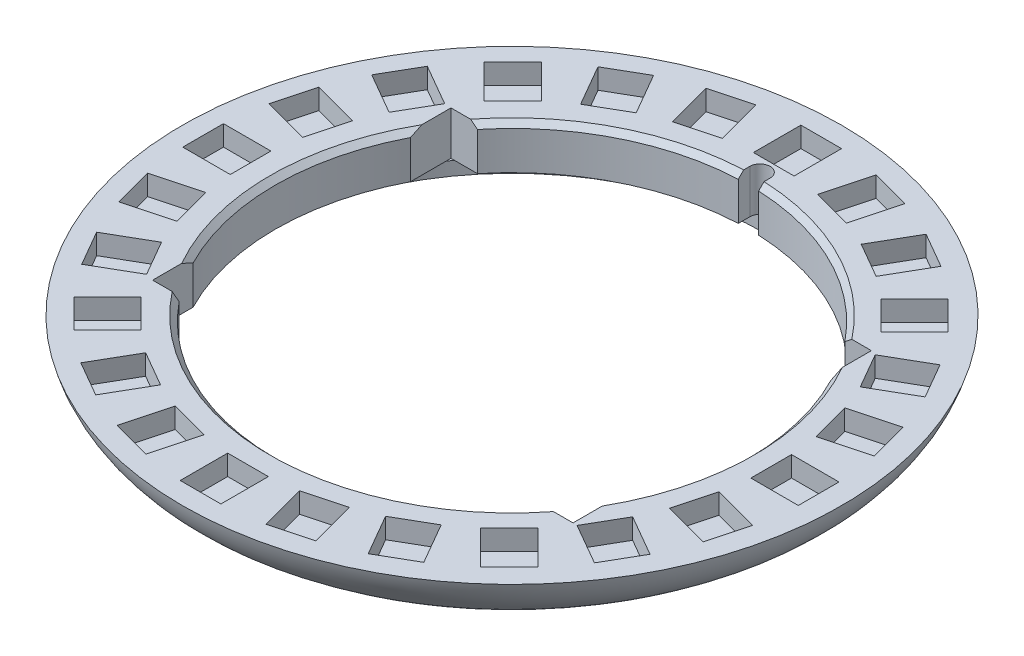
SolidWorks part; units mm, degrees
ref_plane "Plan de face" through (0, 0, 0) normal (0, 0, 1) x (1, 0, 0)
ref_plane "Plan de dessus" through (0, 0, 0) normal (0, 1, 0) x (1, 0, 0)
ref_plane "Plan de droite" through (0, 0, 0) normal (1, 0, 0) x (0, 0, -1)
sketch "Esquisse1" plane through (0, 0, 0) normal (0, 0, 1) x (1, 0, 0)
  line L0 (0, 0) -> (0, 12.722) construction
  line L1 (37.6, 0) -> (37.6, 2)
  line L2 (37.6, 2) -> (34.9, 2)
  line L3 (34.9, 2) -> (34.9, 8.4406)
  line L4 (34.9, 8.4406) -> (48.6, 8.4406)
  line L5 (37.6, 0) -> (39.8723, 0) construction
  line L6 (48.6, 8.4406) -> (47.2112, 3.2577) construction
  line L7 (48.6, 5.228) -> (48.6, 8.4406) construction
  arc A0 (37.6, 0) -> (48.6, 8.4406) centre (37.6, 11.388) ccw
  dimension "D1" = 11
  dimension "D4" = 75
  dimension "D2" = 75.2
  dimension "D3" = 2.7
  dimension "D5" = 2
revolve "Révolution1" add sketch "Esquisse1" angle 360 about L0
sketch "Esquisse2" plane through (0, 8.4406, 0) normal (0, 1, 0) x (1, 0, 0)
  line L1 (-31, -22) -> (31, -22)
  line L2 (-31, -22) -> (-31, 22)
  line L3 (-31, 22) -> (31, 22)
  line L4 (31, -22) -> (31, 22)
  line L5 (-31, -22) -> (31, 22) construction
  line L6 (-31, 22) -> (31, -22) construction
  point P0 (0, 0)
  dimension "D1" = 44
  dimension "D2" = 62
extrude "Enlèv. mat.-Extru.1" cut sketch "Esquisse2" against normal up to surface (6.4406 mm away) up to face at (0, 2, -37.6)
sketch "Esquisse3" plane through (0, 8.4406, 0) normal (0, 1, 0) x (1, 0, 0)
  line L0 (0, 45.6) -> (0, 48.6) construction
  line L1 (-3, 45.6) -> (3, 45.6)
  line L2 (-3, 45.6) -> (-3, 38.6)
  line L3 (-3, 38.6) -> (3, 38.6)
  line L4 (3, 45.6) -> (3, 38.6)
  line L5 (8.8914, 44.7744) -> (14.687, 43.2215)
  line L6 (8.8914, 44.7744) -> (7.0797, 38.0129)
  line L7 (7.0797, 38.0129) -> (12.8753, 36.46)
  line L8 (14.687, 43.2215) -> (12.8753, 36.46)
  line L9 (20.164, 40.8992) -> (25.3601, 37.8992)
  line L10 (20.164, 40.8992) -> (16.664, 34.837)
  line L11 (16.664, 34.837) -> (21.8601, 31.837)
  line L12 (25.3601, 37.8992) -> (21.8601, 31.837)
  line L13 (30.0495, 34.2384) -> (34.2921, 29.9958)
  line L14 (30.0495, 34.2384) -> (25.0997, 29.2887)
  line L15 (25.0997, 29.2887) -> (29.3423, 25.046)
  line L16 (34.2921, 29.9958) -> (29.3423, 25.046)
  line L17 (37.8742, 25.2461) -> (40.8742, 20.05)
  line L18 (37.8742, 25.2461) -> (31.812, 21.7461)
  line L19 (31.812, 21.7461) -> (34.812, 16.55)
  line L20 (40.8742, 20.05) -> (34.812, 16.55)
  line L21 (43.1049, 14.535) -> (44.6578, 8.7395)
  line L22 (43.1049, 14.535) -> (36.3434, 12.7233)
  line L23 (36.3434, 12.7233) -> (37.8963, 6.9277)
  line L24 (44.6578, 8.7395) -> (37.8963, 6.9277)
  line L25 (45.3851, 2.8351) -> (45.3851, -3.1649)
  line L26 (45.3851, 2.8351) -> (38.3851, 2.8351)
  line L27 (38.3851, 2.8351) -> (38.3851, -3.1649)
  line L28 (45.3851, -3.1649) -> (38.3851, -3.1649)
  line L29 (44.5595, -9.0563) -> (43.0066, -14.8519)
  line L30 (44.5595, -9.0563) -> (37.798, -7.2446)
  line L31 (37.798, -7.2446) -> (36.2451, -13.0401)
  line L32 (43.0066, -14.8519) -> (36.2451, -13.0401)
  line L33 (40.6843, -20.3289) -> (37.6843, -25.525)
  line L34 (40.6843, -20.3289) -> (34.6221, -16.8289)
  line L35 (34.6221, -16.8289) -> (31.6221, -22.025)
  line L36 (37.6843, -25.525) -> (31.6221, -22.025)
  line L37 (34.0235, -30.2143) -> (29.7809, -34.457)
  line L38 (34.0235, -30.2143) -> (29.0738, -25.2646)
  line L39 (29.0738, -25.2646) -> (24.8312, -29.5072)
  line L40 (29.7809, -34.457) -> (24.8312, -29.5072)
  line L41 (25.0312, -38.0391) -> (19.8351, -41.0391)
  line L42 (25.0312, -38.0391) -> (21.5312, -31.9769)
  line L43 (21.5312, -31.9769) -> (16.3351, -34.9769)
  line L44 (19.8351, -41.0391) -> (16.3351, -34.9769)
  line L45 (14.3201, -43.2698) -> (8.5246, -44.8227)
  line L46 (14.3201, -43.2698) -> (12.5084, -36.5083)
  line L47 (12.5084, -36.5083) -> (6.7128, -38.0612)
  line L48 (8.5246, -44.8227) -> (6.7128, -38.0612)
  line L49 (2.6202, -45.55) -> (-3.3798, -45.55)
  line L50 (2.6202, -45.55) -> (2.6202, -38.55)
  line L51 (2.6202, -38.55) -> (-3.3798, -38.55)
  line L52 (-3.3798, -45.55) -> (-3.3798, -38.55)
  line L53 (-9.2712, -44.7244) -> (-15.0668, -43.1715)
  line L54 (-9.2712, -44.7244) -> (-7.4595, -37.9629)
  line L55 (-7.4595, -37.9629) -> (-13.255, -36.41)
  line L56 (-15.0668, -43.1715) -> (-13.255, -36.41)
  line L57 (-20.5438, -40.8492) -> (-25.7399, -37.8492)
  line L58 (-20.5438, -40.8492) -> (-17.0438, -34.787)
  line L59 (-17.0438, -34.787) -> (-22.2399, -31.787)
  line L60 (-25.7399, -37.8492) -> (-22.2399, -31.787)
  line L61 (-30.4292, -34.1884) -> (-34.6719, -29.9458)
  line L62 (-30.4292, -34.1884) -> (-25.4795, -29.2387)
  line L63 (-25.4795, -29.2387) -> (-29.7221, -24.996)
  line L64 (-34.6719, -29.9458) -> (-29.7221, -24.996)
  line L65 (-38.2539, -25.1961) -> (-41.2539, -20)
  line L66 (-38.2539, -25.1961) -> (-32.1918, -21.6961)
  line L67 (-32.1918, -21.6961) -> (-35.1918, -16.5)
  line L68 (-41.2539, -20) -> (-35.1918, -16.5)
  line L69 (-43.4847, -14.485) -> (-45.0376, -8.6895)
  line L70 (-43.4847, -14.485) -> (-36.7232, -12.6733)
  line L71 (-36.7232, -12.6733) -> (-38.2761, -6.8777)
  line L72 (-45.0376, -8.6895) -> (-38.2761, -6.8777)
  line L73 (-45.7649, -2.7851) -> (-45.7649, 3.2149)
  line L74 (-45.7649, -2.7851) -> (-38.7649, -2.7851)
  line L75 (-38.7649, -2.7851) -> (-38.7649, 3.2149)
  line L76 (-45.7649, 3.2149) -> (-38.7649, 3.2149)
  line L77 (-44.9393, 9.1063) -> (-43.3864, 14.9019)
  line L78 (-44.9393, 9.1063) -> (-38.1778, 7.2946)
  line L79 (-38.1778, 7.2946) -> (-36.6249, 13.0901)
  line L80 (-43.3864, 14.9019) -> (-36.6249, 13.0901)
  line L81 (-41.0641, 20.3789) -> (-38.0641, 25.575)
  line L82 (-41.0641, 20.3789) -> (-35.0019, 16.8789)
  line L83 (-35.0019, 16.8789) -> (-32.0019, 22.075)
  line L84 (-38.0641, 25.575) -> (-32.0019, 22.075)
  line L85 (-34.4033, 30.2643) -> (-30.1607, 34.507)
  line L86 (-34.4033, 30.2643) -> (-29.4536, 25.3146)
  line L87 (-29.4536, 25.3146) -> (-25.2109, 29.5572)
  line L88 (-30.1607, 34.507) -> (-25.2109, 29.5572)
  line L89 (-25.411, 38.0891) -> (-20.2149, 41.0891)
  line L90 (-25.411, 38.0891) -> (-21.911, 32.0269)
  line L91 (-21.911, 32.0269) -> (-16.7149, 35.0269)
  line L92 (-20.2149, 41.0891) -> (-16.7149, 35.0269)
  line L93 (-14.6999, 43.3198) -> (-8.9044, 44.8727)
  line L94 (-14.6999, 43.3198) -> (-12.8882, 36.5583)
  line L95 (-12.8882, 36.5583) -> (-7.0926, 38.1112)
  line L96 (-8.9044, 44.8727) -> (-7.0926, 38.1112)
  circle A0 centre (0, 0) radius 48.6 construction
  point P4 (0, 38.6)
  point P105 (-0.1899, 0.025)
  dimension "D1" = 6
  dimension "D2" = 7
  dimension "D3" = 3
  dimension "D4" = 24
extrude "Enlèv. mat.-Extru.2" cut sketch "Esquisse3" against normal blind 3
sketch "Esquisse4" plane through (0, 8.4406, 0) normal (0, 1, 0) x (1, 0, 0)
  line L0 (-1.5, 36.5678) -> (-1.5, 34.8678)
  line L1 (-1.5, 34.8678) -> (1.5, 34.8678)
  line L2 (1.5, 34.8678) -> (1.5, 36.5678)
  arc A0 (27.0926, 22) -> (-27.0926, 22) centre (0, 0) ccw construction
  arc A1 (-1.5, 36.5678) -> (1.5, 36.5678) centre (0, 36.5678) cw
  point P9 (0, 34.8678)
  dimension "D1" = 3
  dimension "D2" = 1.7
extrude "Enlèv. mat.-Extru.3" cut sketch "Esquisse4" against normal up to surface (6.4406 mm away) up to face at (0, 2, -29.125)
chamfer "Chanfrein1" distance 0.8 angle 45 5 edges at (-34.9, 8.4406, 0) (0, 8.4406, 34.9) (34.9, 8.4406, 0) (15.6773, 8.4406, -31.1806) (-15.6773, 8.4406, -31.1806)
